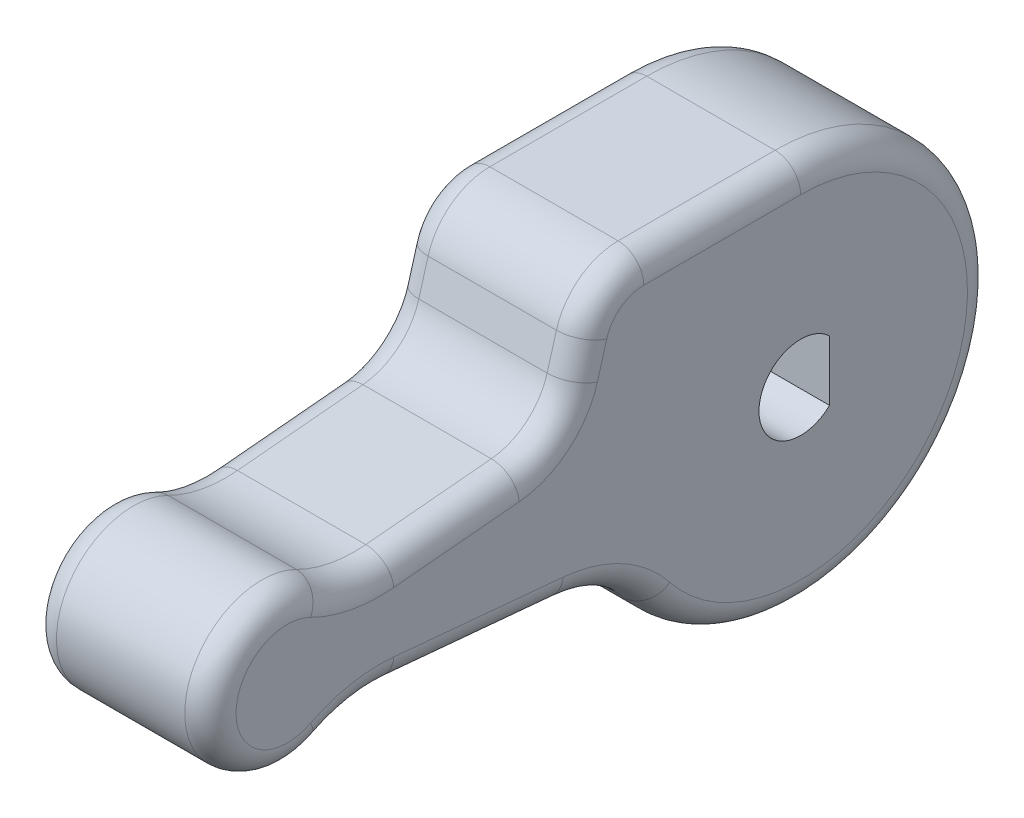
SolidWorks part; units mm, degrees
material "ABS"
ref_plane "Front Plane" through (0, 0, 0) normal (0, 0, 1) x (1, 0, 0)
ref_plane "Top Plane" through (0, 0, 0) normal (0, 1, 0) x (1, 0, 0)
ref_plane "Right Plane" through (0, 0, 0) normal (1, 0, 0) x (0, 0, -1)
sketch "Sketch1" plane through (0, 0, 0) normal (1, 0, 0) x (0, 0, -1)
  line L0 (1.125, -1.1726) -> (1.125, 1.1726)
  line L1 (-23, 0) -> (-20, 0) construction
  line L2 (-20, 0) -> (0, 0) construction
  line L3 (-17.7639, 2) -> (-6.8739, 3)
  line L4 (-17.7639, -2) -> (-6.8739, -3)
  line L5 (0, 0) -> (7.5, 0) construction
  line L6 (-1.625, 0) -> (1.125, 0) construction
  arc A0 (1.125, 1.1726) -> (1.125, -1.1726) centre (0, 0) ccw
  arc A1 (-6.8739, -3) -> (-6.8739, 3) centre (0, 0) ccw
  arc A2 (-17.7639, 2) -> (-17.7639, -2) centre (-20, 0) ccw
  dimension "D1" = 6
  dimension "D2" = 15
  dimension "D4" = 6
  dimension "D6" = 1.625
  dimension "D3" = 23
  dimension "D5" = 4
  dimension "D7" = 2.75
extrude "Boss-Extrude1" add sketch "Sketch1" along normal mid plane 7
fillet "Fillet1" radius 5 4 edges at (0, 2, 17.7639) (0, -3, 6.8739) (0, -2, 17.7639) (0, 3, 6.8739)
ref_plane "Plane1" through (0, 0, -7.625) normal (0, 0, 1) x (1, 0, 0)
hole_wizard "Hole1" positions "Sketch2" profile "Sketch3" legacy
sketch "Sketch2" plane through (0, 0, -7.625) normal (0, 0, 1) x (1, 0, 0)
  point P0 (0, 0)
sketch "Sketch3" plane through (0, 0, -7.625) normal (1, 0, 0) x (0, 1, 0)
  line L0 (0, 0) -> (0, 8)
  line L1 (0, 8) -> (1.25, 8)
  line L2 (1.25, 8) -> (1.25, 3)
  line L3 (1.25, 3) -> (1.75, 3)
  line L4 (1.75, 3) -> (1.75, 0)
  line L5 (1.75, 0) -> (0, 0)
  line L6 (0, 110) -> (0, -10) construction
  dimension "Diameter" = 2.5
  dimension "Depth" = 8
  dimension "C-Bore Diameter" = 3.5
  dimension "C-Bore Depth" = 3
sketch "Sketch4" plane through (3.5, 0, 0) normal (1, 0, 0) x (0, 0, -1)
  line L0 (0, 7.5) -> (-8, 7.5)
  line L1 (-8, 7.5) -> (-9.3489, 2.7727)
  arc A0 (-5.8837, -4.6511) -> (-5.8837, 4.6511) centre (0, 0) ccw construction
  arc A1 (-9.3489, 2.7727) -> (-5.8837, 4.6511) centre (-9.8061, 7.7518) ccw construction
  arc A2 (-9.3489, 2.7727) -> (-5.8837, 4.6511) centre (-9.8061, 7.7518) ccw
  arc A3 (0, 7.5) -> (-5.8837, 4.6511) centre (0, 0) ccw
  dimension "D1" = 8
extrude "Boss-Extrude2" add sketch "Sketch4" against normal through all
fillet "Fillet3" radius 2.5 2 edges at (0, 2.7727, 9.3489) (0, 7.5, 8)
fillet "Fillet2" radius 1 22 edges at (-3.5, -3.356, 7.4234) (-3.5, -2.4698, 12.6476) (-3.5, -2.2335, 17.3348) (-3.5, 0, 23) (-3.5, 2.2335, 17.3348) (-3.5, 2.3915, 13.5003) (3.5, -3.356, 7.4234) (3.5, -2.4698, 12.6476) (3.5, -2.2335, 17.3348) (3.5, 0, 23) (3.5, 2.2335, 17.3348) (3.5, 2.3915, 13.5003) (-3.5, -3.2686, -6.7503) (3.5, -3.2686, -6.7503) (-3.5, 7.5, 3.0568) (3.5, 7.5, 3.0568) (-3.5, 3.181, 9.6874) (-3.5, 5.0528, 8.6983) (3.5, 5.0528, 8.6983) (-3.5, 6.9956, 7.6194) (3.5, 3.181, 9.6874) (3.5, 6.9956, 7.6194)
